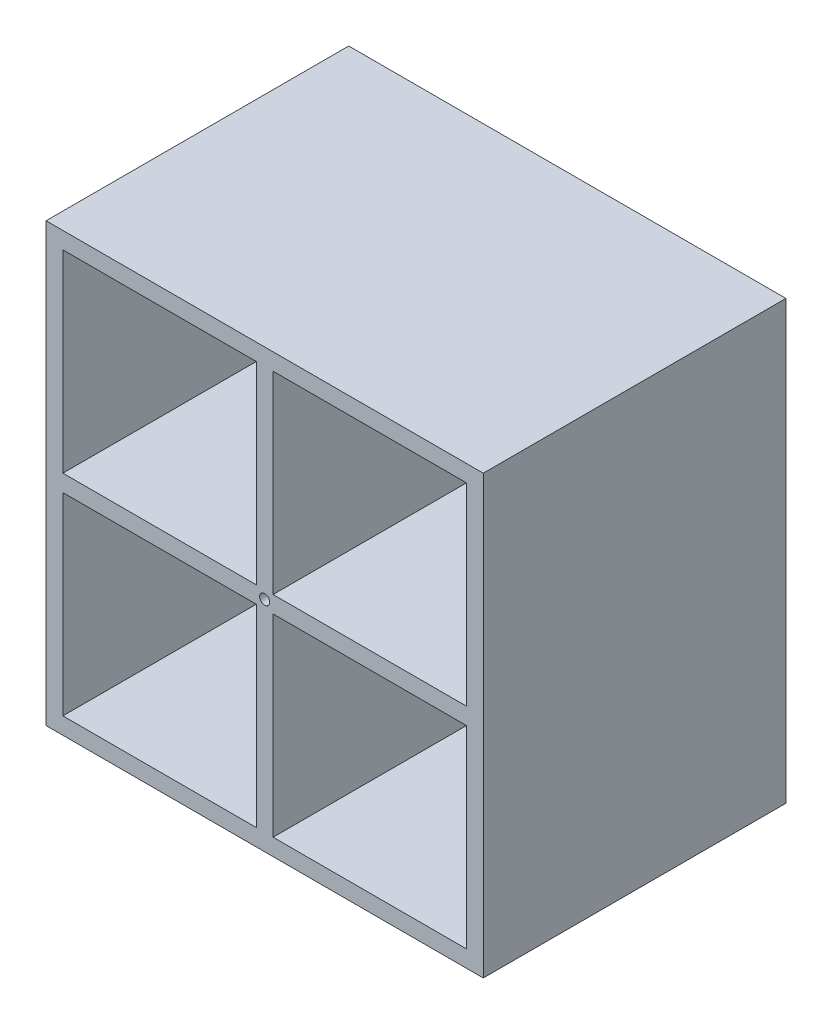
SolidWorks part; units mm, degrees
ref_plane "Přední rovina" through (0, 0, 0) normal (0, 0, 1) x (1, 0, 0)
ref_plane "Horní rovina" through (0, 0, 0) normal (0, 1, 0) x (1, 0, 0)
ref_plane "Pravá rovina" through (0, 0, 0) normal (1, 0, 0) x (0, 0, -1)
sketch "Skica1" plane through (0, 0, 0) normal (0, 0, 1) x (1, 0, 0)
  line L1 (-65, 65) -> (65, 65)
  line L2 (-65, 65) -> (-65, -65)
  line L3 (-65, -65) -> (65, -65)
  line L4 (65, 65) -> (65, -65)
  line L5 (-65, 65) -> (65, -65) construction
  line L6 (-65, -65) -> (65, 65) construction
  point P0 (0, 0)
  dimension "D1" = 130
  dimension "D2" = 130
extrude "Přidat vysunutím1" add sketch "Skica1" along normal blind 90
sketch "Skica3" plane through (0, 0, 90) normal (0, 0, 1) x (1, 0, 0)
  line L0 (-65, -65) -> (65, -65) construction
  line L1 (-60, 2.5) -> (-2.5, 2.5)
  line L2 (-60, 2.5) -> (-60, 60)
  line L3 (-60, 60) -> (-2.5, 60)
  line L4 (-2.5, 2.5) -> (-2.5, 60)
  line L5 (2.5, 2.5) -> (60, 2.5)
  line L6 (2.5, 2.5) -> (2.5, 60)
  line L7 (2.5, 60) -> (60, 60)
  line L8 (60, 2.5) -> (60, 60)
  line L9 (-60, -60) -> (-2.5, -60)
  line L10 (-60, -60) -> (-60, -2.5)
  line L11 (-60, -2.5) -> (-2.5, -2.5)
  line L12 (-2.5, -60) -> (-2.5, -2.5)
  line L13 (2.5, -60) -> (60, -60)
  line L14 (2.5, -60) -> (2.5, -2.5)
  line L15 (2.5, -2.5) -> (60, -2.5)
  line L16 (60, -60) -> (60, -2.5)
  line L17 (65, 65) -> (-65, 65) construction
  line L18 (-65, 65) -> (-65, -65) construction
  line L19 (65, -65) -> (65, 65) construction
  dimension "D1" = 57.5
  dimension "D2" = 5
  dimension "D3" = 5
  dimension "D4" = 5
  dimension "D5" = 5
  dimension "D6" = 5
  dimension "D7" = 5
  dimension "D8" = 5
  dimension "D9" = 5
extrude "Odebrat vysunutím1" cut sketch "Skica3" against normal blind 90
sketch "Skica4" plane through (0, 0, 90) normal (0, 0, 1) x (1, 0, 0)
  line L0 (-65, -65) -> (65, -65) construction
  circle A0 centre (0, 0) radius 1.5
  dimension "D1" = 3
  dimension "D2" = 65
extrude "Odebrat vysunutím2" cut sketch "Skica4" against normal blind 90
